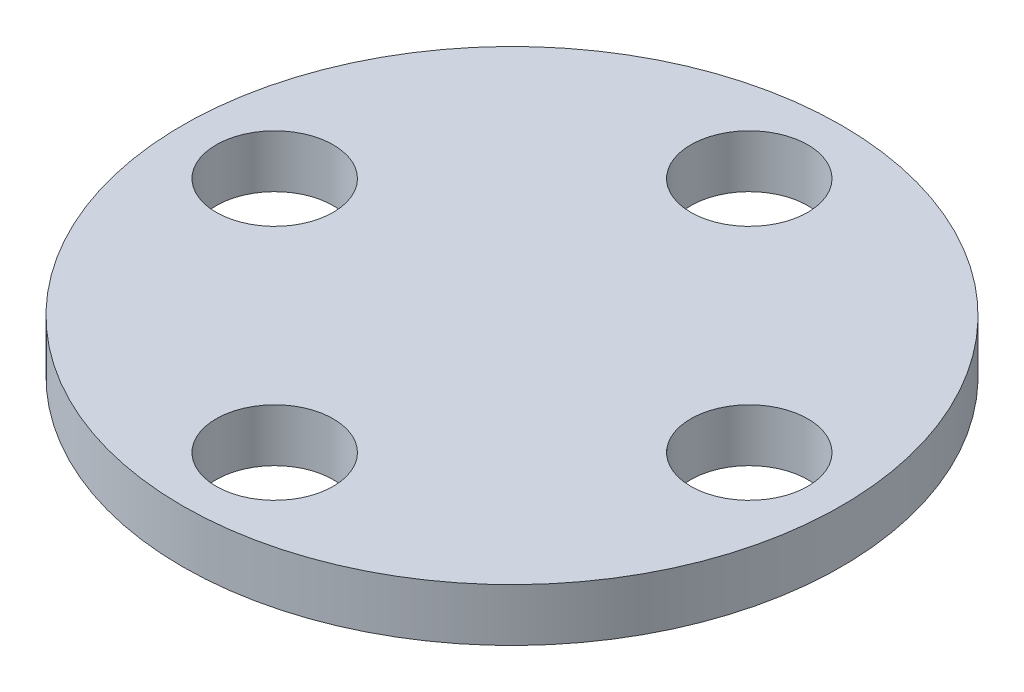
SolidWorks part; units mm, degrees
ref_plane "Front Plane" through (0, 0, 0) normal (0, 0, 1) x (1, 0, 0)
ref_plane "Top Plane" through (0, 0, 0) normal (0, 1, 0) x (1, 0, 0)
ref_plane "Right Plane" through (0, 0, 0) normal (1, 0, 0) x (0, 0, -1)
sketch "Sketch1" plane through (0, 0, 0) normal (0, 1, 0) x (1, 0, 0)
  circle A0 centre (0, 0) radius 15.875
  dimension "D1" = 31.75
extrude "Boss-Extrude1" add sketch "Sketch1" along normal blind 2.54
sketch "Sketch2" plane through (0, 2.54, 0) normal (0, 1, 0) x (1, 0, 0)
  line L0 (0, 0) -> (0, 11.43) construction
  circle A0 centre (0, 0) radius 11.43 construction
  circle A1 centre (0, 11.43) radius 2.8194
  circle A2 centre (11.43, 0) radius 2.8194
  circle A3 centre (0, -11.43) radius 2.8194
  circle A4 centre (-11.43, 0) radius 2.8194
  dimension "D1" = 22.86
  dimension "D2" = 5.6388
  dimension "D4" = 11.43
  dimension "D3" = 4
extrude "Cut-Extrude1" cut sketch "Sketch2" against normal blind 2.54
